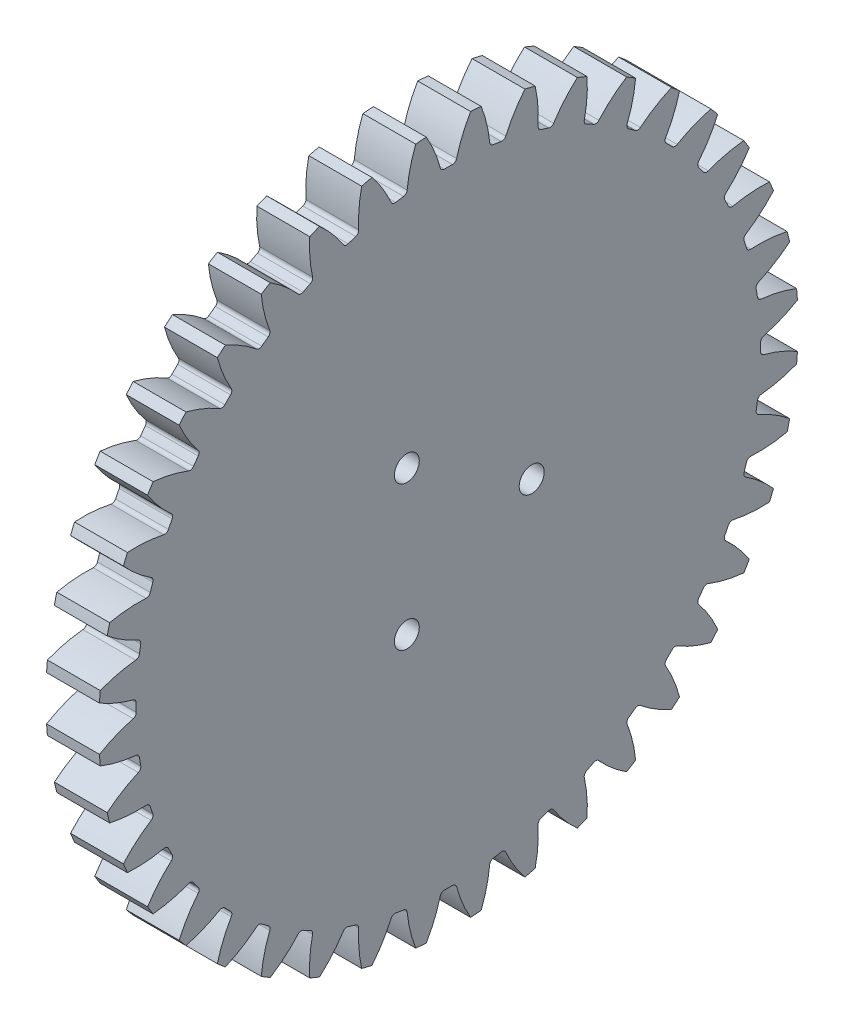
SolidWorks part; units mm, degrees
material "Delrin 2700 NC010, Low Viscosity Acetal Copolymer (SS)"
ref_plane "Plane1" through (0, 0, 0) normal (0, 0, 1) x (1, 0, 0)
ref_plane "Plane2" through (0, 0, 0) normal (0, 1, 0) x (1, 0, 0)
ref_plane "Plane3" through (0, 0, 0) normal (1, 0, 0) x (0, 0, -1)
sketch "HoldingSke" plane through (0, 0, 0) normal (0, 1, 0) x (1, 0, 0)
  line L0 (0, 0) -> (0.383, -0.3214)
  line L1 (-15, 0) -> (100, 0) construction
  line L2 (0, 0) -> (-2.1039, 2.3779)
  line L3 (0, 0) -> (-11.863, 4.5341)
  line L4 (0, 0) -> (6.6156, 5.5511)
  line L5 (0, 0) -> (-46.8476, -17.4728)
  line L6 (0, 0) -> (-4.1448, -2.7965)
  line L7 (-2.1039, 2.3779) -> (8.6586, 51.2059)
  line L8 (-76.2, 54.61) -> (-76.1, 54.61)
  line L9 (-71.009, 38.7566) -> (-53.1078, 45.2721)
  line L10 (-76.2, 71.12) -> (104.1128, 71.12)
  line L11 (0, 0) -> (-5, 0)
  line L12 (-76.2, 101.6) -> (-76.133, 101.6)
  line L13 (24.9733, 27.94) -> (52.9518, 28.4284)
  line L14 (24.9733, 27.94) -> (24.9743, 27.94)
  line L15 (24.9733, 27.94) -> (100.4006, 29.5858)
  line L16 (-63.627, -2) -> (-12.827, -2)
  circle A0 centre (0, 0) radius 0.4
  circle A1 centre (0, 0) radius 37.499
  circle A2 centre (0, 0) radius 37.5
  circle A3 centre (0, 0) radius 0.4
  dimension "MHD" = 74.998
  dimension "Hub_dia" = 75
  dimension "Bore" = 0.8
  dimension "MBD" = 0.8
  dimension "Num_teeth" = 40
  dimension "Pitch" = 0.5
  dimension "Overall_len" = 50
  dimension "Show_teeth" = 40
  dimension "Thickness" = 5
  dimension "OAL" = 50.0001
  dimension "T_dim" = 0.1
  dimension "Ap" = 20
  dimension "H" = 19.05
  dimension "Pitch_radius" = 180.3128
  dimension "Width" = 5
  dimension "Backlash" = 0.067
  dimension "Addendum_fac" = 1
  dimension "Dedendum_fac" = 1.25
  dimension "Clearance_fac" = 0.25
  dimension "Dedendum_add" = 0.001
  dimension "Module" = 2
sketch "BasProSke" plane through (0, 0, 0) normal (0, 1, 0) x (1, 0, 0)
  line L0 (-10, 0) -> (60, 0) construction
  line L1 (0, 0) -> (0, 42)
  line L2 (0, 0) -> (6.35, 0)
  line L3 (6.35, 0) -> (6.35, 42)
  line L4 (6.35, 42) -> (0, 42)
  dimension "Thickness" = 6.35
  dimension "Diameter" = 84
revolve "Base-Revolve" add sketch "BasProSke" angle 360 about L0
sketch "TooCutSke" plane through (0, 0, 0) normal (1, 0, 0) x (0, 0, -1)
  line L1 (0, 0) -> (0, 107) construction
  line L2 (0, 0) -> (-1.6876, 39.9644) construction
  line L3 (0, 0) -> (-6.2726, 79.7007) construction
  line L4 (-1.6876, 39.9644) -> (-3.1363, 39.8504) construction
  arc A0 (0.8828, 37.4886) -> (-0.8828, 37.4886) centre (0, 0) ccw
  arc A1 (2.6784, 41.94) -> (-2.6784, 41.94) centre (0, 0) ccw
  circle A2 centre (0, 0) radius 40 construction
  circle A3 centre (0, 0) radius 37.5877 construction
  arc A4 (-0.8828, 37.4886) -> (-2.6784, 41.94) centre (-16.451, 33.7965) ccw
  arc A5 (2.6784, 41.94) -> (0.8828, 37.4886) centre (16.451, 33.7965) ccw
  dimension "Root_dia" = 74.998
  dimension "Overcut_dia" = 84.0508
  dimension "Pitch_dia" = 80
  dimension "Base_dia" = 75.1754
  dimension "Flank_rad" = 16
  dimension "Half_ang" = 4.5
  dimension "Half_CT" = 1.4531
extrude "ToothCut" cut sketch "TooCutSke" along normal through all
fillet "Breaks" [suppressed] radius 0.04
fillet "RootFillets" radius 0.501 2 edges at (3.175, 37.4886, -0.8828) (3.175, 37.4886, 0.8828)
pattern_circular "TeethCuts" count 40 every 9 about axis through (-10, 0, 0) along (1, 0, 0) of "ToothCut", "RootFillets", "Breaks"
sketch "HubNeaOneSke" plane through (0, 0, 0) normal (-1, 0, 0) x (0, 0, 1)
  circle A0 centre (0, 0) radius 37.499
  dimension "Diameter" = 74.998
extrude "HubNearOne" [suppressed] add sketch "HubNeaOneSke" along normal blind 43.6501
sketch "HubNeaBotSke" plane through (0, 0, 0) normal (-1, 0, 0) x (0, 0, 1)
  circle A0 centre (0, 0) radius 37.499
  dimension "Diameter" = 74.998
extrude "HubNearBoth" [suppressed] add sketch "HubNeaBotSke" along normal blind 21.825
ref_plane "FarPln" through (6.35, 0, 0) normal (1, 0, 0) x (0, 0, -1)
sketch "HubFarSke" plane through (6.35, 0, 0) normal (1, 0, 0) x (0, 0, -1)
  circle A0 centre (0, 0) radius 37.499
  dimension "Diameter" = 74.998
extrude "HubFar" [suppressed] add sketch "HubFarSke" along normal blind 21.825
sketch "BorSke" plane through (0, 0, 0) normal (1, 0, 0) x (0, 0, -1)
  circle A0 centre (0, 0) radius 0.4
  dimension "Diameter" = 0.8
extrude "Bore" [suppressed] cut sketch "BorSke" along normal mid plane 100.0001
sketch "KeySke" plane through (0, 0, 0) normal (1, 0, 0) x (0, 0, -1)
  line L0 (-0.05, 0) -> (-0.05, 0.5)
  line L1 (-0.05, 0.5) -> (0.05, 0.5)
  line L2 (0.05, 0.5) -> (0.05, 0)
  line L3 (0, 0) -> (0, 34) construction
  line L4 (-0.05, 0) -> (0.05, 0)
  dimension "Offset" = 0.5
  dimension "Width" = 0.1
extrude "Keyway" [suppressed] cut sketch "KeySke" along normal mid plane 100.0001
pattern_circular "Keyway2" [suppressed] count 2 every 90 about axis through (-10, 0, 0) along (1, 0, 0)
sketch "Sketch1" plane through (6.35, 0, 0) normal (1, 0, 0) x (0, 0, -1)
  line L0 (0, 0) -> (10, 0)
  line L1 (0, 0) -> (-5, 8.6603)
  line L2 (0, 0) -> (-5, -8.6603)
  circle A0 centre (-5, -8.6603) radius 1.5
  circle A1 centre (-5, 8.6603) radius 1.5
  circle A2 centre (10, 0) radius 1.5
  dimension "D6" = 3
  dimension "D7" = 3
  dimension "D8" = 3
  dimension "D1" = 10
  dimension "D2" = 10
  dimension "D3" = 10
  dimension "D4" = 120
  dimension "D5" = 120
extrude "Cut-Extrude1" cut sketch "Sketch1" against normal through all contours A2 | A0 | A1
equation "' \"Module@HoldingSke\" = 6.35"
equation "' \"Num_teeth@HoldingSke\" = 12"
equation "' \"Ap@HoldingSke\" =  20"
equation "' \"Ap@HoldingSke\" = 20"
equation "' \"Width@HoldingSke\" = 0.5 * 25.4"
equation "' \"Hub_dia@HoldingSke\"= 1 * 25.4"
equation "' \"Hub_dia@HoldingSke\" = 1 * 25.4"
equation "' \"Overall_len@HoldingSke\" = 1.0 * 25.4"
equation "' \"Bore@HoldingSke\" = 0.75 * 25.4"
equation "' \"T_dim@HoldingSke\" = 0.1 * 25.4"
equation "' \"Width@KeySke\" = 0.25 * 25.4"
equation "' \"Show_teeth@HoldingSke\" = 13"
equation "' \"Backlash@HoldingSke\" = 0.009 * 25.4"
equation "' \"Addendum_fac@HoldingSke\" = 1.0"
equation "' \"Dedendum_fac@HoldingSke\" = 1.25"
equation "' \"Dedendum_add@HoldingSke\" = 0.00005 * 25.4"
equation "' \"Clearance_fac@HoldingSke\" = 0.25"
equation "\"Pitch@HoldingSke\" = 1 / \"Module@HoldingSke\""
equation "\"Overcut_dia@TooCutSke\" = (\"Num_teeth@HoldingSke\" + 2 * \"Addendum_fac@HoldingSke\") / \"Pitch@HoldingSke\" + 0.002 * 25.4"
equation "\"Pitch_dia@TooCutSke\" = \"Num_teeth@HoldingSke\" / \"Pitch@HoldingSke\""
equation "\"Base_dia@TooCutSke\" = \"Num_teeth@HoldingSke\" / \"Pitch@HoldingSke\" * cos((\"Ap@HoldingSke\"  * 3.14159265 / 180))"
equation "\"Root_dia@TooCutSke\" = (\"Num_teeth@HoldingSke\" + 2) / \"Pitch@HoldingSke\" - 2 * (\"Addendum_fac@HoldingSke\" + \"Dedendum_fac@HoldingSke\") / \"Pitch@HoldingSke\" - \"Dedendum_add@HoldingSke\" * 2"
equation "\"Half_ang@TooCutSke\" = 180 / \"Num_teeth@HoldingSke\""
equation "\"Half_CT@TooCutSke\" = \"Num_teeth@HoldingSke\" / \"Pitch@HoldingSke\" * sin((3.14159265 / 2 / \"Num_teeth@HoldingSke\")) / 2 - 7 * \"Backlash@HoldingSke\" / 4"
equation "\"Flank_rad@TooCutSke\" = \"Num_teeth@HoldingSke\" / \"Pitch@HoldingSke\" / 5"
equation "\"Radius@RootFillets\" = \"Clearance_fac@HoldingSke\" / \"Pitch@HoldingSke\" + \"Dedendum_add@HoldingSke\""
equation "\"Break_rad@Breaks\" = 0.02 / \"Pitch@HoldingSke\""
equation "\"Thickness@HoldingSke\" = \"Width@HoldingSke\""
equation "\"OAL@HoldingSke\" = \"Thickness@HoldingSke\""
equation "\"MHD@HoldingSke\" = (\"Num_teeth@HoldingSke\" + 2) / \"Pitch@HoldingSke\" - 2 * (\"Addendum_fac@HoldingSke\" + \"Dedendum_fac@HoldingSke\")  / \"Pitch@HoldingSke\" - \"Dedendum_add@HoldingSke\" * 2"
equation "\"MBD@HoldingSke\" = (\"Num_teeth@HoldingSke\" + 2) / \"Pitch@HoldingSke\" - 2 * (\"Addendum_fac@HoldingSke\" + \"Dedendum_fac@HoldingSke\")  / \"Pitch@HoldingSke\" - \"Dedendum_add@HoldingSke\" * 2 - 0.002 * 25.4"
equation "\"MHD@HoldingSke\" = ((sgn( \"MHD@HoldingSke\" - \"Hub_dia@HoldingSke\" )-1)*( \"MHD@HoldingSke\" - \"Hub_dia@HoldingSke\" ))/-2+ \"Hub_dia@HoldingSke\""
equation "\"MBD@HoldingSke\" = ((sgn( \"MBD@HoldingSke\" - \"Bore@HoldingSke\" )-1)*( \"MBD@HoldingSke\" - \"Bore@HoldingSke\" ))/-2+ \"Bore@HoldingSke\""
equation "\"OAL@HoldingSke\" = ((sgn( \"OAL@HoldingSke\" - \"Overall_len@HoldingSke\" )+1)*( \"OAL@HoldingSke\" - \"Overall_len@HoldingSke\" ))/2 + \"Overall_len@HoldingSke\" + 0.000002 * 25.4"
equation "\"Num_teeth@TeethCuts\" = int( \"Show_teeth@HoldingSke\" ) + 1"
equation "\"Num_teeth@TeethCuts\" = ((sgn( \"Num_teeth@TeethCuts\" - \"Num_teeth@HoldingSke\" )-1)*( \"Num_teeth@TeethCuts\" - \"Num_teeth@HoldingSke\" ))/-2+ \"Num_teeth@HoldingSke\""
equation "\"Num_teeth@TeethCuts\" = ((sgn( \"Num_teeth@TeethCuts\" - 2.0)+1)*( \"Num_teeth@TeethCuts\" - 2.0))/2 +2.0"
equation "\"Angle@TeethCuts\" = 360.0 / \"Num_teeth@HoldingSke\""
equation "\"Diameter@BasProSke\" = (\"Num_teeth@HoldingSke\" + 2 * \"Addendum_fac@HoldingSke\") / \"Pitch@HoldingSke\""
equation "\"Thickness@BasProSke\"=6.35mm"
equation "' \"Fillet_rad@BasProSke\" =  \"Thickness@HoldingSke\" * 0.05"
equation "' \"Fillet_rad@BasProSke\" = \"Thickness@HoldingSke\" * 0.05"
equation "\"MHD@HoldingSke\" = ((sgn( \"MHD@HoldingSke\" - \"Root_dia@TooCutSke\" )-1)*( \"MHD@HoldingSke\" - \"Root_dia@TooCutSke\" ))/-2+ \"Root_dia@TooCutSke\""
equation "\"Diameter@HubNeaOneSke\" = \"MHD@HoldingSke\""
equation "\"Length@HubNearOne\" = \"OAL@HoldingSke\" - \"Thickness@BasProSke\""
equation "\"Diameter@HubNeaBotSke\" = \"MHD@HoldingSke\""
equation "\"Length@HubNearBoth\" = ( \"OAL@HoldingSke\" - \"Thickness@BasProSke\" ) / 2.0"
equation "\"Thickness@FarPln\" = \"Thickness@BasProSke\""
equation "\"Diameter@HubFarSke\" = \"MHD@HoldingSke\""
equation "\"Length@HubFar\" = ( \"OAL@HoldingSke\" - \"Thickness@BasProSke\" ) / 2.0"
equation "\"Diameter@BorSke\" = \"MBD@HoldingSke\""
equation "\"D1@Bore\" = \"OAL@HoldingSke\" * 2.0"
equation "\"D1@Keyway\" = \"OAL@HoldingSke\" * 2.0"
equation "\"Offset@KeySke\" = \"T_dim@HoldingSke\" + \"MBD@HoldingSke\" / 2.0"
